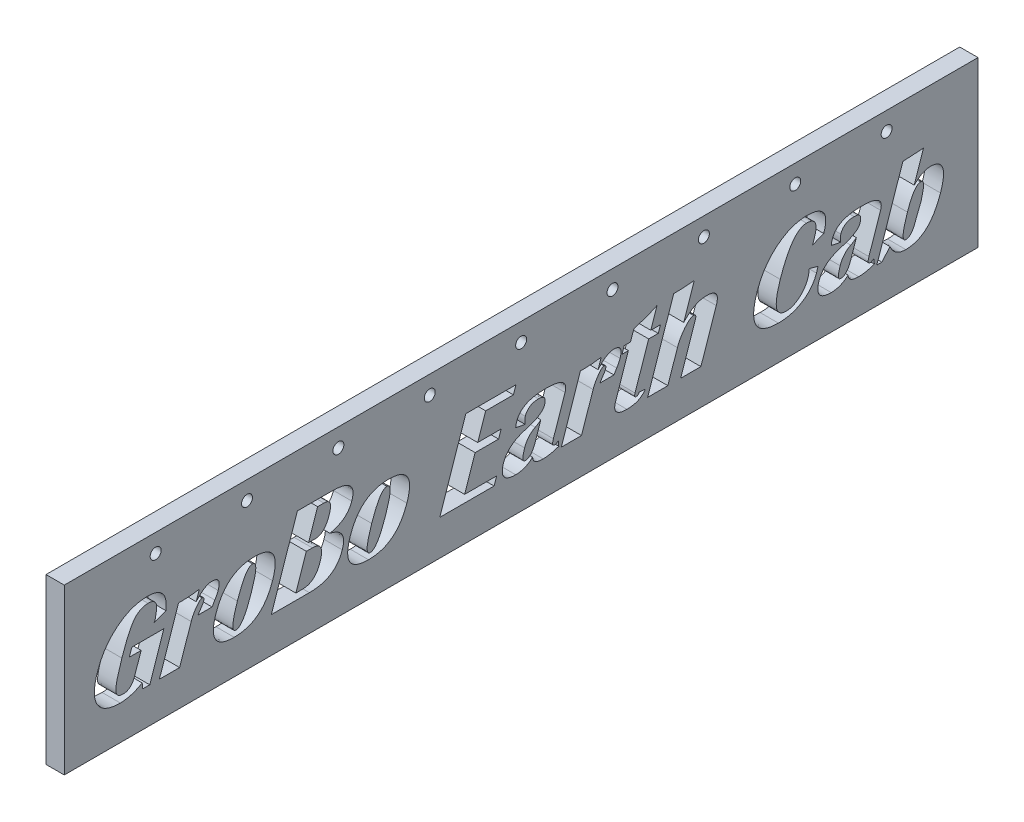
SolidWorks part; units mm, degrees
material "Acrylic (Medium-high impact)"
ref_plane "Front Plane" through (0, 0, 0) normal (0, 0, 1) x (1, 0, 0)
ref_plane "Top Plane" through (0, 0, 0) normal (0, 1, 0) x (1, 0, 0)
ref_plane "Right Plane" through (0, 0, 0) normal (1, 0, 0) x (0, 0, -1)
sketch "Sketch1" plane through (0, 0, 0) normal (0, 0, 1) x (1, 0, 0)
  line L6 (25, 5) -> (25, 95)
  line L7 (25, 95) -> (15, 95)
  line L8 (15, 95) -> (15, 5)
  line L12 (15, 5) -> (25, 5)
  dimension "D1" = 10
extrude "Boss-Extrude1" add sketch "Sketch1" along normal blind 500
sketch "Sketch2" plane through (25, 0, 0) normal (1, 0, 0) x (0, 0, -1)
  line L0 (-1052.1126, 85) -> (45.5589, 85) construction
  line L1 (-500, 95) -> (-475, 95)
  line L2 (-500, 95) -> (-500, 70)
  line L3 (-500, 70) -> (-475, 70)
  line L4 (-475, 95) -> (-475, 70)
  line L5 (0, 95) -> (-25, 95)
  line L6 (0, 95) -> (0, 70)
  line L7 (0, 70) -> (-25, 70)
  line L8 (-25, 95) -> (-25, 70)
  line L9 (-500, 95) -> (0, 95) construction
  dimension "D1" = 25
  dimension "D2" = 25
  dimension "D3" = 25
  dimension "D4" = 25
  dimension "D5" = 10
extrude "Cut-Extrude1" [suppressed] cut sketch "Sketch2" against normal blind 10
sketch "Sketch3" [suppressed] plane through (25, 0, 0) normal (1, 0, 0) x (0, 0, -1)
  line L0 (-995, 70) -> (-995, 95) construction
  line L1 (-995, 95) -> (-25, 95) construction
  circle A0 centre (-898, 85) radius 3
  dimension "D3" = 6
  dimension "D1" = 97
  dimension "D2" = 10
extrude "Cut-Extrude2" [suppressed] cut sketch "Sketch3" against normal blind 10
pattern_linear "LPattern1" [suppressed] count 9 spacing 97
ref_plane "Plane1" through (0, 0, 250) normal (0, 0, -1) x (-1, 0, 0)
sketch "Sketch4" plane through (25, 0, 0) normal (1, 0, 0) x (0, 0, -1)
  line L0 (-500, 95) -> (0, 95) construction
  line L2 (-500, 5) -> (-500, 95) construction
  circle A0 centre (-450, 85) radius 3
  dimension "D2" = 6
  dimension "D1" = 10
  dimension "D3" = 50
extrude "Cut-Extrude3" cut sketch "Sketch4" against normal blind 10
pattern_linear "LPattern2" count 9 spacing 50 along (0, 0, -1) of "Cut-Extrude3"
sketch "Sketch5" plane through (25, 0, 0) normal (1, 0, 0) x (0, 0, -1)
  text T0 "GroBo Earth Cab" font "Britannic Bold" height 42
extrude "Cut-Extrude4" cut sketch "Sketch5" against normal blind 10
